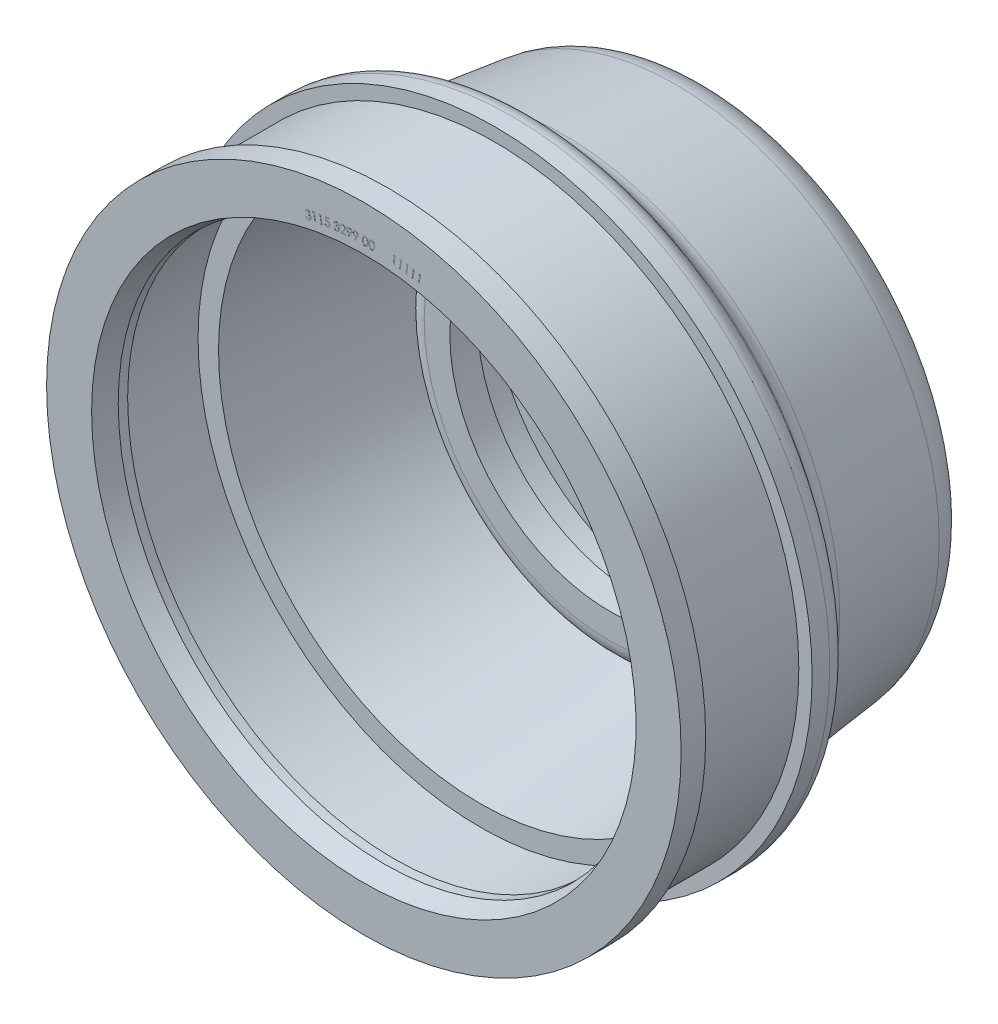
SolidWorks part; units mm, degrees
material "TPU-95A"
ref_plane "Front Plane" through (0, 0, 0) normal (0, 0, 1) x (1, 0, 0)
ref_plane "Top Plane" through (0, 0, 0) normal (0, 1, 0) x (1, 0, 0)
ref_plane "Right Plane" through (0, 0, 0) normal (1, 0, 0) x (0, 0, -1)
sketch "Sketch1" plane through (0, 0, 0) normal (1, 0, 0) x (0, 0, -1)
  line L0 (0, 39) -> (0, 54.3941)
  line L1 (-8.791, 64.3207) -> (-36.4781, 67.6928)
  line L2 (-9.5, 55.403) -> (-9.5, 56.7052) construction
  line L3 (-40.5345, 70.0247) -> (-44.6994, 75.5201)
  line L4 (-48.6843, 77.5) -> (-53, 77.5)
  line L5 (-53, 77.5) -> (-53, 74.25)
  line L6 (-53, 74.25) -> (-79, 74.25)
  line L7 (-79, 74.25) -> (-79, 77.5)
  line L8 (-79, 77.5) -> (-85, 77.5)
  line L9 (-85, 77.5) -> (-85, 66.5)
  line L11 (-77.7, 65) -> (-77.7, 69)
  line L12 (-77.7, 69) -> (-56.5, 69)
  line L13 (-56.5, 69) -> (-56.5, 64)
  line L14 (-77.7, 65) -> (-80, 65)
  line L15 (-56.5, 64) -> (-12.053, 58.8649)
  line L16 (-21.535, 50.0177) -> (-11.4986, 53.2553)
  line L17 (-80, 65) -> (-85, 66.5)
  line L18 (-25, 45.2592) -> (-25, 39)
  line L19 (-25, 39) -> (-18.3, 39)
  line L20 (-18.3, 39) -> (-18.3, 46)
  line L21 (-18.3, 46) -> (-8.2, 46)
  line L22 (-8.2, 46) -> (-8.2, 39)
  line L23 (-8.2, 39) -> (0, 39)
  line L24 (0, 0) -> (-115, 0) construction
  arc A0 (-12.053, 58.8649) -> (-11.4986, 53.2553) centre (-12.384, 56) cw
  arc A1 (-25, 45.2592) -> (-21.535, 50.0177) centre (-20, 45.2592) cw
  arc A2 (-40.5345, 70.0247) -> (-36.4781, 67.6928) centre (-35.7527, 73.6488) ccw
  arc A5 (-8.791, 64.3207) -> (0, 54.3941) centre (-10, 54.3941) cw
  arc A6 (-48.6843, 77.5) -> (-44.6994, 75.5201) centre (-48.6843, 72.5) cw
  point P27 (-39, 68)
  point P30 (-25, 48.9)
  point P33 (-9.5, 53.9)
  point P36 (-9.5, 58.57)
  point P41 (0, 63.25)
  point P44 (-46.2, 77.5)
  dimension "D22" = 10
  dimension "D27" = 5
  dimension "D28" = 107.8
  dimension "D24" = 75.5
  dimension "D13" = 6
  dimension "D17" = 5
  dimension "D29" = 5
  dimension "D26" = 112
  dimension "D1" = 85
  dimension "D2" = 155
  dimension "D3" = 130
  dimension "D4" = 133
  dimension "D5" = 7.3
  dimension "D6" = 78
  dimension "D7" = 25
  dimension "D8" = 126.5
  dimension "D9" = 39
  dimension "D10" = 136
  dimension "D11" = 28.5
  dimension "D12" = 46.2
  dimension "D14" = 6
  dimension "D15" = 26
  dimension "D16" = 148.5
  dimension "D18" = 138
  dimension "D19" = 92
  dimension "D20" = 8.2
  dimension "D21" = 10.1
  dimension "D23" = 128
  dimension "D25" = 97.8
revolve "Revolve1" add sketch "Sketch1" angle 360 about L24
sketch "Sketch2" plane through (0, 0, 85) normal (0, 0, 1) x (1, 0, 0)
  arc A0 (-68.4402, 0) -> (68.4402, 0) centre (0, 0) cw construction
  text T0 "3115 3299 00     11111"
  dimension "D1" = 68.4402
extrude "Cut-Extrude1" cut sketch "Sketch2" against normal blind 0.01
